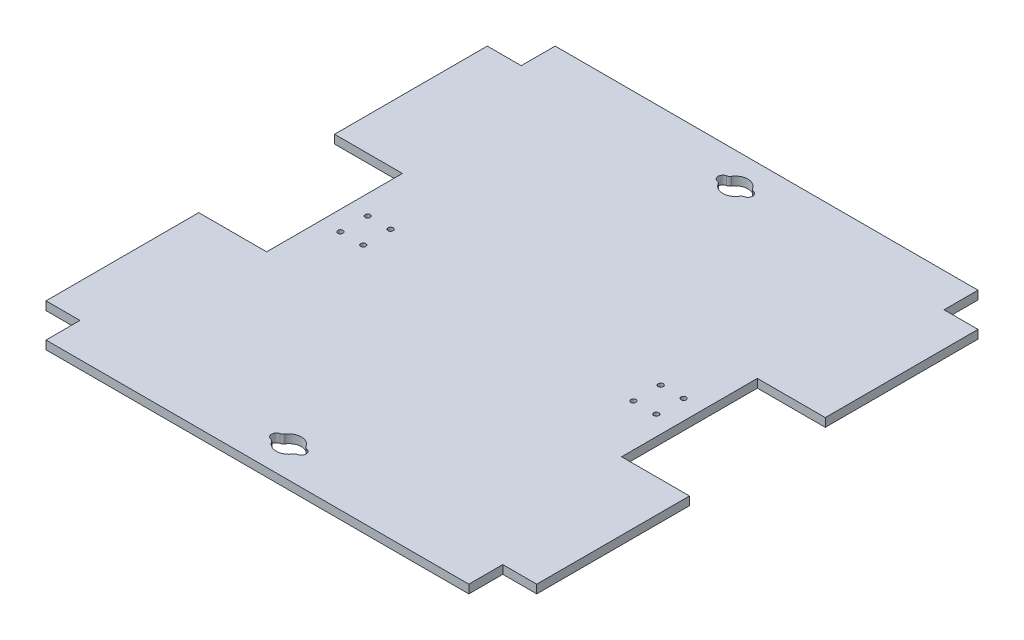
SolidWorks part; units mm, degrees
ref_plane "Plan de face" through (0, 0, 0) normal (0, 0, 1) x (1, 0, 0)
ref_plane "Plan de dessus" through (0, 0, 0) normal (0, 1, 0) x (1, 0, 0)
ref_plane "Plan de droite" through (0, 0, 0) normal (1, 0, 0) x (0, 0, -1)
sketch "Esquisse1" plane through (0, 0, 0) normal (0, 1, 0) x (1, 0, 0)
  line L0 (-174.5839, 0) -> (222.3951, 0) construction
  line L1 (-144.5683, 40) -> (-104.5683, 40)
  line L2 (-104.5683, 40) -> (-104.5683, -40)
  line L3 (-144.5683, -40) -> (-104.5683, -40)
  line L4 (0, 143.2846) -> (0, -128.3979) construction
  line L5 (144.5683, -40) -> (104.5683, -40)
  line L6 (104.5683, 40) -> (104.5683, -40)
  line L7 (144.5683, 40) -> (104.5683, 40)
  line L8 (-144.5683, -40) -> (-144.5683, -150)
  line L9 (-144.5683, -150) -> (144.5683, -150)
  line L10 (144.5683, -150) -> (144.5683, -40)
  line L11 (-144.5683, 40) -> (-144.5683, 150)
  line L12 (-144.5683, 150) -> (144.5683, 150)
  line L13 (144.5683, 150) -> (144.5683, 40)
  line L14 (-144.5683, 130) -> (-124.5683, 130)
  line L15 (-124.5683, 130) -> (-124.5683, 150)
  line L16 (144.5683, 130) -> (124.5683, 130)
  line L17 (124.5683, 130) -> (124.5683, 150)
  line L18 (124.5683, -130) -> (124.5683, -150)
  line L19 (144.5683, -130) -> (124.5683, -130)
  line L20 (-124.5683, -130) -> (-124.5683, -150)
  line L21 (-144.5683, -130) -> (-124.5683, -130)
  circle A0 centre (0, 0) radius 150
  point P9 (-104.5683, 0)
  dimension "D1" = 300
  dimension "D2" = 40
  dimension "D3" = 40
  dimension "D10" = 20
  dimension "D11" = 20
extrude "Boss.-Extru.1" add sketch "Esquisse1" along normal blind 5 contours L7 A0 L1 L2 L3 L5 L6 | A0 L12 L11 | A0 L13 L12 | A0 L8 L9 | A0 L9 L10
sketch "Esquisse2" plane through (0, 5, 0) normal (0, 1, 0) x (1, 0, 0)
  line L0 (72.9219, 0) -> (-206.4046, 0) construction
  circle A0 centre (-93.0683, 8.0429) radius 1.5 construction
  circle A1 centre (-93.0683, -8.0429) radius 1.5 construction
  circle A2 centre (-79.5683, -8.0429) radius 1.5 construction
  circle A3 centre (-79.5683, 8.0429) radius 1.5 construction
  circle A4 centre (93.0683, -8.0429) radius 1.5 construction
  circle A5 centre (79.5683, -8.0429) radius 1.5 construction
  circle A6 centre (79.5683, 8.0429) radius 1.5 construction
  circle A7 centre (93.0683, 8.0429) radius 1.5 construction
  circle A8 centre (-93.0683, 8.0429) radius 1.5
  circle A9 centre (-93.0683, -8.0429) radius 1.5
  circle A10 centre (-79.5683, -8.0429) radius 1.5
  circle A11 centre (-79.5683, 8.0429) radius 1.5
  circle A12 centre (93.0683, -8.0429) radius 1.5
  circle A13 centre (79.5683, -8.0429) radius 1.5
  circle A14 centre (79.5683, 8.0429) radius 1.5
  circle A15 centre (93.0683, 8.0429) radius 1.5
  arc A16 (7.97, -128.8112) -> (6.3113, -127.6617) centre (8.4684, -126.3206) cw
  arc A17 (-6.1998, -127.6617) -> (6.3113, -127.6617) centre (0.0558, -131.5509) cw
  arc A18 (-6.1998, -127.6617) -> (-7.8585, -128.8112) centre (-8.3569, -126.3206) cw
  arc A19 (-7.8585, -134.2906) -> (-7.8585, -128.8112) centre (-7.3102, -131.5509) cw
  arc A20 (-7.8585, -134.2906) -> (-6.1998, -135.4401) centre (-8.3569, -136.7812) cw
  arc A21 (6.3113, -135.4401) -> (-6.1998, -135.4401) centre (0.0558, -131.5509) cw
  arc A22 (6.3113, -135.4401) -> (7.97, -134.2906) centre (8.4684, -136.7812) cw
  arc A23 (7.97, -128.8112) -> (7.97, -134.2906) centre (7.4218, -131.5509) cw
  arc A24 (7.97, 128.8112) -> (7.97, 134.2906) centre (7.4218, 131.5509) ccw
  arc A25 (6.3113, 135.4401) -> (7.97, 134.2906) centre (8.4684, 136.7812) ccw
  arc A26 (6.3113, 135.4401) -> (-6.1998, 135.4401) centre (0.0558, 131.5509) ccw
  arc A27 (-7.8585, 134.2906) -> (-6.1998, 135.4401) centre (-8.3569, 136.7812) ccw
  arc A28 (-7.8585, 134.2906) -> (-7.8585, 128.8112) centre (-7.3102, 131.5509) ccw
  arc A29 (-6.1998, 127.6617) -> (-7.8585, 128.8112) centre (-8.3569, 126.3206) ccw
  arc A30 (-6.1998, 127.6617) -> (6.3113, 127.6617) centre (0.0558, 131.5509) ccw
  arc A31 (7.97, 128.8112) -> (6.3113, 127.6617) centre (8.4684, 126.3206) ccw
  arc A32 (7.97, 128.8112) -> (7.97, 134.2906) centre (7.4218, 131.5509) ccw
  arc A33 (6.3113, 135.4401) -> (7.97, 134.2906) centre (8.4684, 136.7812) ccw
  arc A34 (6.3113, 135.4401) -> (-6.1998, 135.4401) centre (0.0558, 131.5509) ccw
  arc A35 (-7.8585, 134.2906) -> (-6.1998, 135.4401) centre (-8.3569, 136.7812) ccw
  arc A36 (-7.8585, 134.2906) -> (-7.8585, 128.8112) centre (-7.3102, 131.5509) ccw
  arc A37 (-6.1998, 127.6617) -> (-7.8585, 128.8112) centre (-8.3569, 126.3206) ccw
  arc A38 (-6.1998, 127.6617) -> (6.3113, 127.6617) centre (0.0558, 131.5509) ccw
  arc A39 (7.97, 128.8112) -> (6.3113, 127.6617) centre (8.4684, 126.3206) ccw
  dimension "D1" = 0
sketch "Esquisse3" plane through (0, 5, 0) normal (0, 1, 0) x (1, 0, 0)
  line L0 (0, 195.6319) -> (0, -165.5054) construction
extrude "Enlèv. mat.-Extru.1" cut sketch "Esquisse2" against normal blind 10
